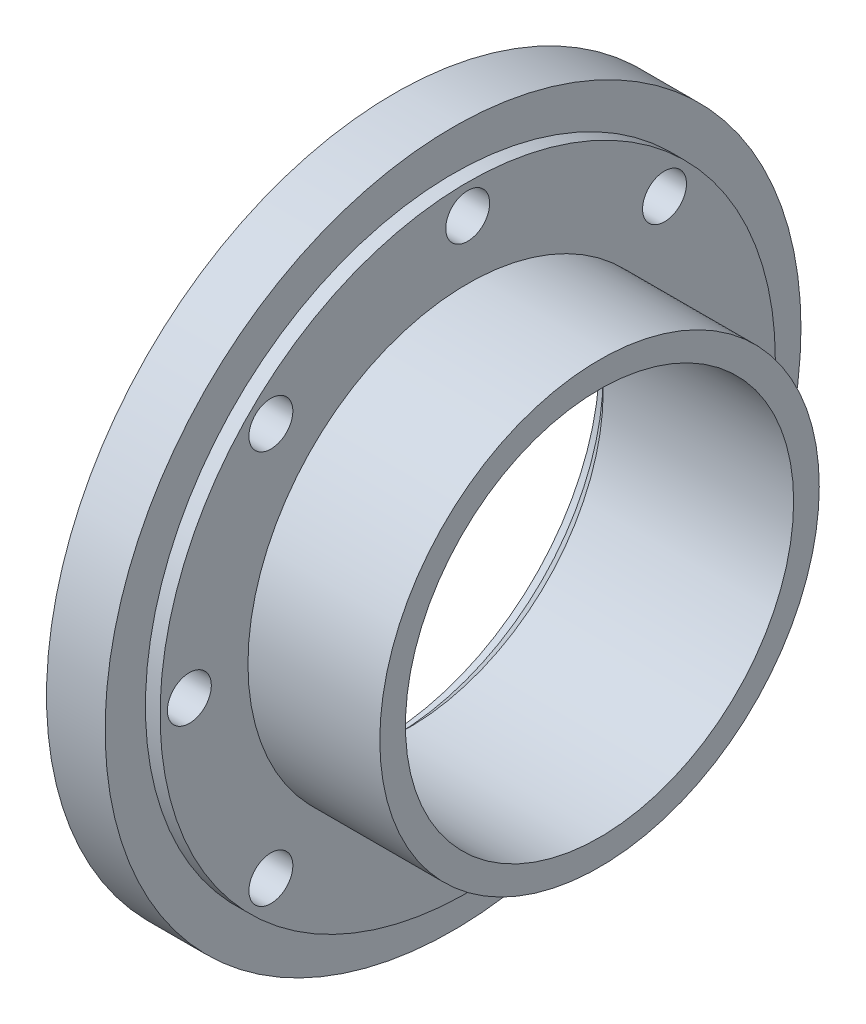
SolidWorks part; units mm, degrees
ref_plane "前视基准面" through (0, 0, 0) normal (0, 0, 1) x (1, 0, 0)
ref_plane "上视基准面" through (0, 0, 0) normal (0, 1, 0) x (1, 0, 0)
ref_plane "右视基准面" through (0, 0, 0) normal (1, 0, 0) x (0, 0, -1)
other "Configuration Table"
sketch "草图1" plane through (0, 0, 0) normal (0, 0, 1) x (1, 0, 0)
  line L0 (0, 0) -> (0, 34)
  line L1 (0, 34) -> (2, 34)
  line L2 (2, 34) -> (2, 47.5)
  line L3 (2, 47.5) -> (10, 47.5)
  line L4 (10, 47.5) -> (10, 42)
  line L5 (10, 42) -> (12, 42)
  line L6 (12, 42) -> (12, 30)
  line L7 (12, 30) -> (30, 30)
  line L8 (30, 30) -> (30, 0)
  line L9 (30, 0) -> (0, 0)
  line L10 (0, 0) -> (-20.5581, 0) construction
  dimension "D1" = 68
  dimension "D2" = 95
  dimension "D3" = 84
  dimension "D4" = 60
  dimension "D5" = 2
  dimension "D6" = 8
  dimension "D7" = 10
  dimension "D8" = 30
revolve "旋转1" add sketch "草图1" angle 360 about L10
sketch "草图2" plane through (0, 0, 0) normal (0, 0, 1) x (1, 0, 0)
  line L0 (0, 0) -> (-22.3526, 0) construction
  line L1 (0, 0) -> (0, 30)
  line L2 (0, 34) -> (0, -34) construction
  line L3 (0, 30) -> (2, 30)
  line L4 (2, 30) -> (2, 26.5)
  line L5 (2, 26.5) -> (30, 26.5)
  line L6 (30, -30) -> (30, 30) construction
  line L7 (30, 26.5) -> (30, 0)
  line L8 (30, 0) -> (0, 0)
  dimension "D1" = 60
  dimension "D2" = 53
  dimension "D3" = 2
revolve "切除-旋转1" cut sketch "草图2" angle 360 about L0
sketch "草图3" plane through (12, 0, 0) normal (1, 0, 0) x (0, 0, -1)
  circle A0 centre (0, 0) radius 38 construction
  circle A1 centre (0, 38) radius 3
  circle A2 centre (26.8701, 26.8701) radius 3
  circle A3 centre (38, 0) radius 3
  circle A4 centre (26.8701, -26.8701) radius 3
  circle A5 centre (0, -38) radius 3
  circle A6 centre (-26.8701, -26.8701) radius 3
  circle A7 centre (-38, 0) radius 3
  circle A8 centre (-26.8701, 26.8701) radius 3
  point P6 (0, 0)
  point P7 (38, 0)
  point P21 (0, 0)
  dimension "D1" = 76
  dimension "D2" = 6
  dimension "D3" = 8
extrude "切除-拉伸1" cut sketch "草图3" against normal up to next
chamfer "倒角1" distance 2 angle 45 1 edges at (2, 0, -26.5)
